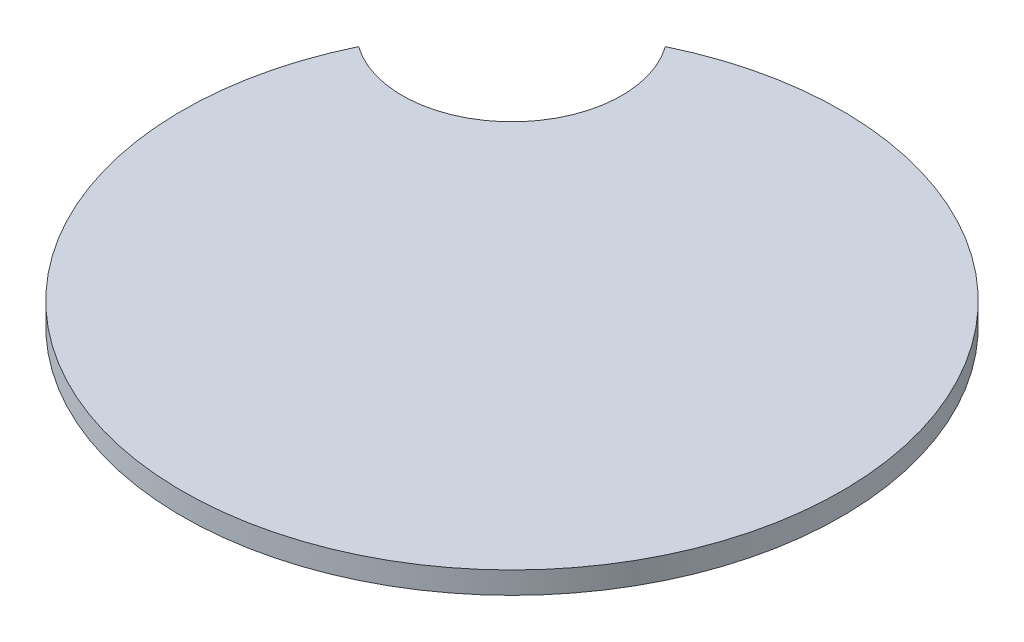
SolidWorks part; units mm, degrees
ref_plane "Ebene vorne" through (0, 0, 0) normal (0, 0, 1) x (1, 0, 0)
ref_plane "Ebene oben" through (0, 0, 0) normal (0, 1, 0) x (1, 0, 0)
ref_plane "Ebene rechts" through (0, 0, 0) normal (1, 0, 0) x (0, 0, -1)
sketch "Skizze1" plane through (0, 0, 0) normal (0, 1, 0) x (1, 0, 0)
  circle A0 centre (0, 0) radius 10
  dimension "D1" = 20
extrude "Aufsatz-Linear austragen1" add sketch "Skizze1" against normal blind 2
sketch "Skizze2" plane through (0, 0, 0) normal (0, 1, 0) x (1, 0, 0)
  circle A0 centre (0, 0) radius 30
  dimension "D1" = 60
extrude "Aufsatz-Linear austragen2" add sketch "Skizze2" along normal blind 2
sketch "Skizze3" plane through (0, -2, 0) normal (0, -1, 0) x (1, 0, 0)
  line L0 (-7.0711, 7.0711) -> (-9.1924, 9.1924)
  line L1 (7.0711, 7.0711) -> (9.1924, 9.1924)
  line L2 (7.0711, -7.0711) -> (9.1924, -9.1924)
  line L3 (-7.0711, -7.0711) -> (-9.1924, -9.1924)
  arc A0 (9.1924, 9.1924) -> (9.1924, -9.1924) centre (0, 0) cw
  arc A1 (-9.1924, 9.1924) -> (-9.1924, -9.1924) centre (0, 0) ccw
  circle A2 centre (0, 0) radius 10 construction
  circle A3 centre (0, 0) radius 10 construction
  arc A4 (-7.0711, 7.0711) -> (-7.0711, -7.0711) centre (0, 0) ccw
  arc A5 (7.0711, 7.0711) -> (7.0711, -7.0711) centre (0, 0) cw
extrude "Aufsatz-Linear austragen3" add sketch "Skizze3" along normal blind 2 separate body
sketch "Skizze4" plane through (0, -2, 0) normal (0, -1, 0) x (1, 0, 0)
  circle A0 centre (0, 0) radius 10
extrude "Aufsatz-Linear austragen4" add sketch "Skizze4" along normal blind 2
sketch "Skizze8" plane through (0, -2, 0) normal (0, 1, 0) x (1, 0, 0)
  line L0 (9.1924, -9.1924) -> (7.0711, -7.0711) construction
  line L1 (10.0765, -8.2136) -> (7.7376, -6.3348)
  line L2 (9.1924, -9.1924) -> (7.0711, -7.0711)
  line L3 (-7.0711, 7.0711) -> (-9.1924, 9.1924)
  line L4 (-10.0575, 8.2369) -> (-7.7328, 6.3407)
  arc A0 (7.0711, -7.0711) -> (7.7376, -6.3348) centre (0, 0) ccw
  arc A1 (9.1924, -9.1924) -> (10.0765, -8.2136) centre (0, 0) ccw
  arc A2 (-7.0711, 7.0711) -> (-7.7328, 6.3407) centre (0, 0) ccw
  arc A3 (-9.1924, 9.1924) -> (-10.0575, 8.2369) centre (0, 0) ccw
extrude "Aufsatz-Linear austragen15" add sketch "Skizze8" along normal blind 3
sketch "Skizze9" plane through (0, 0, 0) normal (0, -1, 0) x (1, 0, 0)
  line L0 (-7.0711, -7.0711) -> (-22.4094, -22.4094) construction
  line L1 (-9.1924, -9.1924) -> (-7.0711, -7.0711) construction
  arc A0 (-7.0711, -7.0711) -> (7.7376, 6.3348) centre (0, 0) ccw construction
  circle A1 centre (-21.1767, -21.1767) radius 10
extrude "Schnitt-Linear austragen1" cut sketch "Skizze9" against normal blind 10
sketch "Skizze10" plane through (0, 0, 0) normal (0, -1, 0) x (1, 0, 0)
  line L0 (12.75, 0) -> (13, 0)
  line L1 (11.2506, 5.9989) -> (11.4748, 6.1097)
  line L2 (9.5353, -8.4641) -> (9.7308, -8.6204)
  line L3 (12.5964, -1.9732) -> (12.844, -2.0081)
  line L4 (-12.7319, -0.0177) -> (-12.9819, -0.0177)
  line L5 (-11.2338, -6.0166) -> (-11.458, -6.1274)
  line L6 (-9.5266, 8.4572) -> (-9.7221, 8.6136)
  line L7 (-12.5861, 1.9651) -> (-12.8336, 1.9999)
  circle A0 centre (0, 0) radius 13 construction
  circle A1 centre (0, 0) radius 12.75 construction
  arc A2 (11.4748, 6.1097) -> (13, 0) centre (0, 0) cw
  arc A3 (11.2506, 5.9989) -> (12.75, 0) centre (0, 0) cw
  arc A4 (12.844, -2.0081) -> (9.7308, -8.6204) centre (0, 0) cw
  arc A5 (12.5964, -1.9732) -> (9.5353, -8.4641) centre (0, 0) cw
  arc A6 (-11.458, -6.1274) -> (-12.9819, -0.0177) centre (0.0355, -0.0159) cw
  arc A7 (-11.2338, -6.0166) -> (-12.7319, -0.0177) centre (0.0355, -0.0159) cw
  arc A8 (-12.8336, 1.9999) -> (-9.7221, 8.6136) centre (0.0355, -0.0159) cw
  arc A9 (-12.5861, 1.9651) -> (-9.5266, 8.4572) centre (0.0355, -0.0159) cw
extrude "Aufsatz-Linear austragen16" add sketch "Skizze10" along normal blind 3
